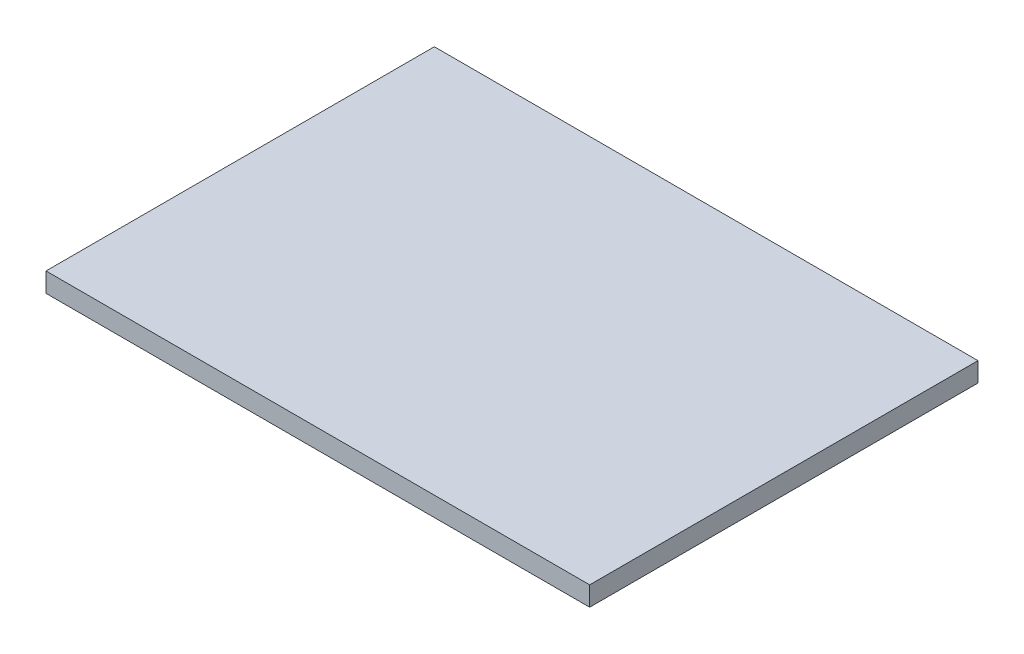
SolidWorks part; units mm, degrees
ref_plane "Alzado" through (0, 0, 0) normal (0, 0, 1) x (1, 0, 0)
ref_plane "Planta" through (0, 0, 0) normal (0, 1, 0) x (1, 0, 0)
ref_plane "Vista lateral" through (0, 0, 0) normal (1, 0, 0) x (0, 0, -1)
ref_plane "Plano_BaseFijaPlataforma" through (0, 0, 0) normal (0, 1, 0) x (1, 0, 0)
sketch "SkBaseFijaPlataforma" plane through (0, 0, 0) normal (0, 1, 0) x (1, 0, 0)
  line L1 (-350, -250) -> (350, -250)
  line L2 (-350, -250) -> (-350, 250)
  line L3 (-350, 250) -> (350, 250)
  line L4 (350, -250) -> (350, 250)
extrude "BaseFijaPlataforma" add sketch "SkBaseFijaPlataforma" along normal blind 25 separate body
